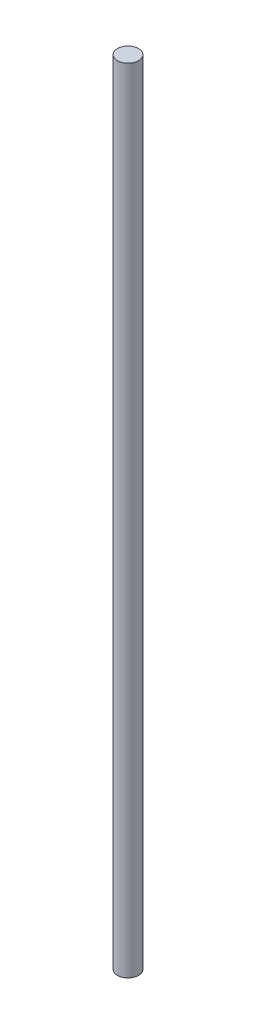
SolidWorks part; units mm, degrees
material "3.0526 (EN-AW 3004)"
ref_plane "前视基准面" through (0, 0, 0) normal (0, 0, 1) x (1, 0, 0)
ref_plane "上视基准面" through (0, 0, 0) normal (0, 1, 0) x (1, 0, 0)
ref_plane "右视基准面" through (0, 0, 0) normal (1, 0, 0) x (0, 0, -1)
sketch "草图1" plane through (0, 0, 0) normal (0, 1, 0) x (1, 0, 0)
  circle A0 centre (0, 0) radius 2
extrude "凸台-拉伸1" add sketch "草图1" along normal blind 150
sketch "草图2" plane through (0, 0, 0) normal (1, 0, 0) x (0, 0, -1)
  line L0 (0, 0) -> (0, 150)
  line L1 (2, 150) -> (-2, 150) construction
